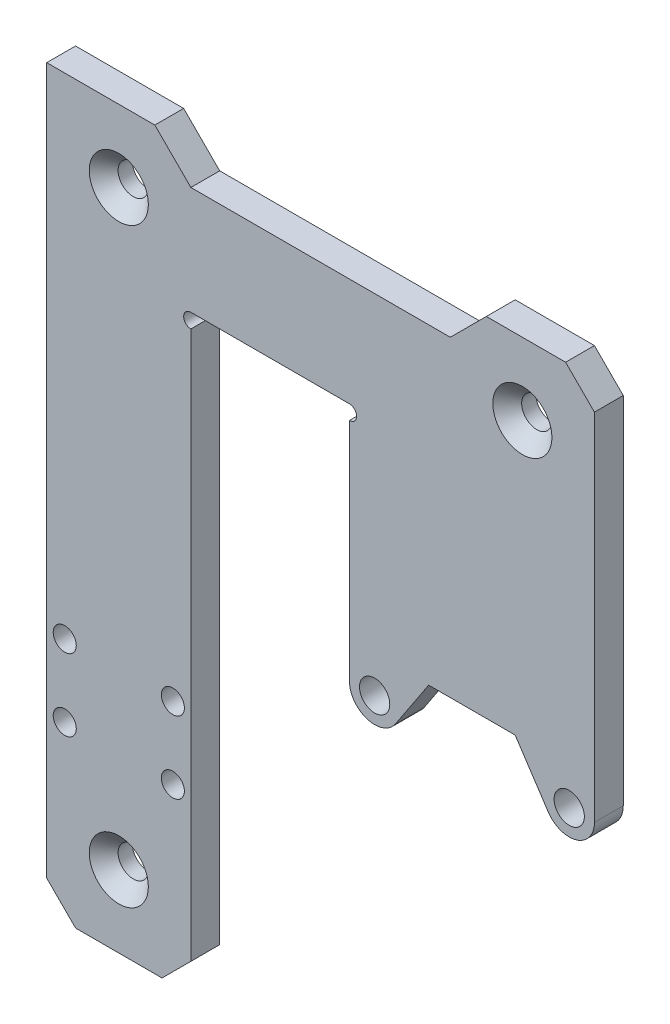
SolidWorks part; units mm, degrees
ref_plane "前视基准面" through (0, 0, 0) normal (0, 0, 1) x (1, 0, 0)
ref_plane "上视基准面" through (0, 0, 0) normal (0, 1, 0) x (1, 0, 0)
ref_plane "右视基准面" through (0, 0, 0) normal (1, 0, 0) x (0, 0, -1)
sketch "草图1" plane through (0, 0, 0) normal (0, 0, 1) x (1, 0, 0)
  line L0 (11, 0) -> (-11, 0)
  line L1 (11, 0) -> (11, -33.3066)
  line L3 (45, -33.3066) -> (45, 20)
  line L4 (45, 20) -> (-31, 20)
  line L5 (-31, 20) -> (-31, -82)
  line L6 (-11, 0) -> (-11, -82)
  line L7 (-31, -82) -> (-11, -82)
  line L8 (-21, -82) -> (-21, 20) construction
  line L9 (28, -37.8238) -> (28, 20) construction
  line L10 (17.4199, -35.2364) -> (22, -28.3066)
  line L11 (38.78, -72.4) -> (17.22, -72.4) construction
  line L12 (47, -64.18) -> (47, -45.22) construction
  line L13 (38.78, -37) -> (17.22, -37) construction
  line L14 (9, -64.18) -> (9, -45.22) construction
  line L15 (47, -72.4) -> (9, -37) construction
  line L16 (47, -37) -> (9, -72.4) construction
  line L17 (22, -28.3066) -> (34, -28.3066)
  line L18 (38.5801, -35.2364) -> (34, -28.3066)
  line L19 (-11, -22) -> (11, -22) construction
  circle A0 centre (-21, 10) radius 2.1
  circle A1 centre (35, 10) radius 2.1
  circle A2 centre (14.5, -33.3066) radius 2.1
  circle A3 centre (41.5, -33.3066) radius 2.1
  arc A4 (11, -33.3066) -> (17.4199, -35.2364) centre (14.5, -33.3066) ccw
  arc A5 (38.5801, -35.2364) -> (45, -33.3066) centre (41.5, -33.3066) ccw
  arc A6 (17.22, -72.4) -> (9, -64.18) centre (17.22, -64.18) cw construction
  arc A7 (38.78, -72.4) -> (47, -64.18) centre (38.78, -64.18) ccw construction
  arc A8 (47, -45.22) -> (38.78, -37) centre (38.78, -45.22) ccw construction
  arc A9 (17.22, -37) -> (9, -45.22) centre (17.22, -45.22) ccw construction
  circle A10 centre (14.5, -33.3066) radius 4 construction
  circle A11 centre (41.5, -33.3066) radius 4 construction
  circle A12 centre (-21, -72) radius 2.1
  point P0 (28, -54.7)
  point P4 (0, 0)
  point P47 (28, -28.3066)
  dimension "D5" = 4.2
  dimension "D6" = 10
  dimension "D8" = 37
  dimension "D9" = 3.5
  dimension "D10" = 3.5
  dimension "D11" = 4.2
  dimension "D12" = 38
  dimension "D2" = 34
  dimension "D14" = 8.22
  dimension "D15" = 8
  dimension "D20" = 10
  dimension "D21" = 10
  dimension "D3" = 49
  dimension "D4" = 22
  dimension "D7" = 20
  dimension "D13" = 35.4
  dimension "D16" = 6
  dimension "D17" = 5
  dimension "D18" = 22
  dimension "D19" = 60
extrude "凸台-拉伸1" add sketch "草图1" along normal mid plane 4
sketch "草图3" plane through (0, 0, 2) normal (0, 0, 1) x (1, 0, 0)
  line L0 (-16, 20) -> (-11, 15)
  line L1 (45, 20) -> (-31, 20) construction
  line L2 (-11, 15) -> (25, 15)
  line L3 (25, 15) -> (30, 20)
  line L4 (-11, 0) -> (11, 0) construction
  line L5 (-16, 20) -> (30, 20)
  circle A0 centre (-21, 10) radius 2.1 construction
  circle A1 centre (35, 10) radius 2.1 construction
  dimension "D1" = 15
  dimension "D2" = 10
  dimension "D3" = 45
  dimension "D4" = 10
extrude "切除-拉伸1" cut sketch "草图3" against normal through all
chamfer "倒角1" distance 2 angle 45 3 edges at (37.1, 10, 2) (-18.9, 10, 2) (-18.9, -72, 2)
sketch "草图4" plane through (0, 0, 2) normal (0, 0, 1) x (1, 0, 0)
  line L0 (-11, -82) -> (-11, 0) construction
  line L1 (11, 0) -> (11, -33.3066) construction
  circle A0 centre (-11, -1) radius 1
  circle A1 centre (11, -1) radius 1
  dimension "D1" = 2
extrude "切除-拉伸2" cut sketch "草图4" against normal through all
chamfer "倒角2" distance 4 angle 45 3 edges at (45, 20, 0) (-31, -82, 0) (-11, -82, 0)
sketch "草图7" plane through (0, 0, 2) normal (0, 0, 1) x (1, 0, 0)
  line L0 (-27, -82) -> (-15, -82) construction
  line L1 (-13.5, -58) -> (-28.5, -58) construction
  line L2 (-13.5, -58) -> (-13.5, -48) construction
  line L3 (-13.5, -48) -> (-28.5, -48) construction
  line L4 (-28.5, -58) -> (-28.5, -48) construction
  line L5 (-13.5, -58) -> (-28.5, -48) construction
  line L6 (-13.5, -48) -> (-28.5, -58) construction
  circle A0 centre (-21, -72) radius 2.1 construction
  circle A1 centre (-28.5, -48) radius 1.6
  circle A2 centre (-28.5, -58) radius 1.6
  circle A3 centre (-13.5, -48) radius 1.6
  circle A4 centre (-13.5, -58) radius 1.6
  point P0 (-21, -53)
  point P8 (-21, -82)
  dimension "D4" = 3.2
  dimension "D1" = 15
  dimension "D2" = 10
  dimension "D3" = 19
extrude "切除-拉伸3" cut sketch "草图7" against normal through all
